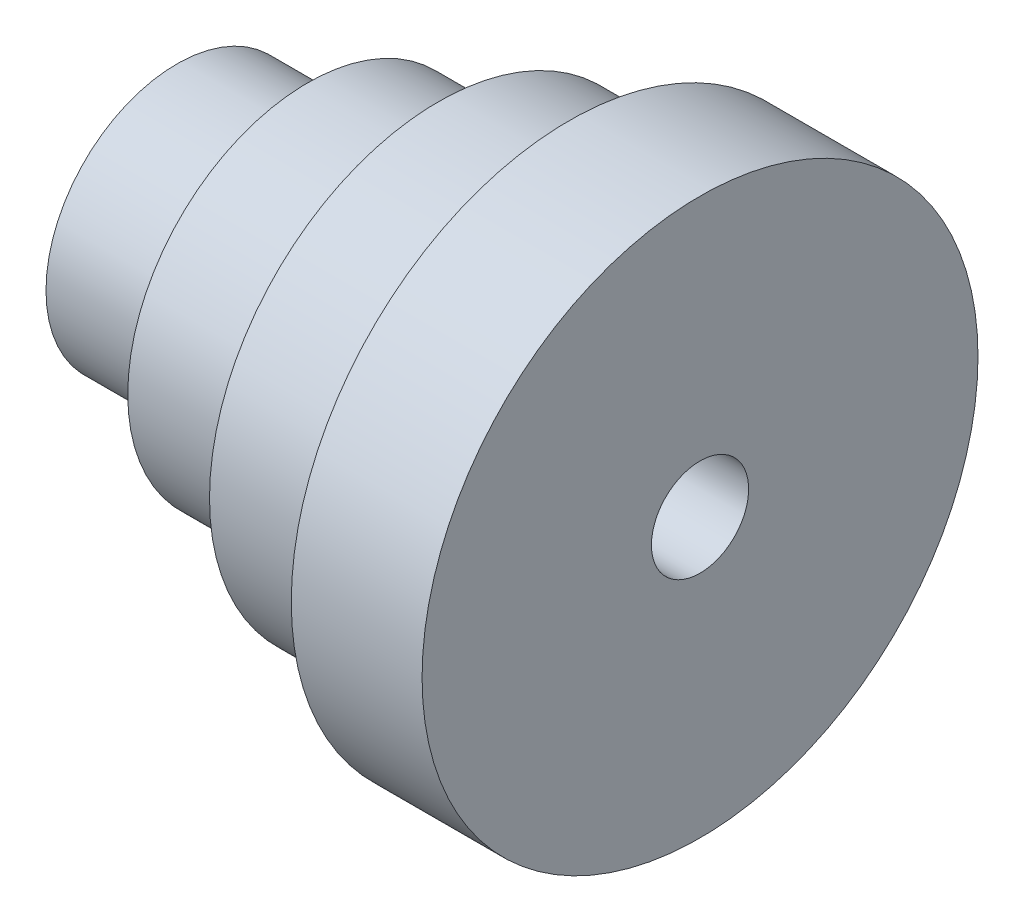
SolidWorks part; units mm, degrees
ref_plane "Front Plane" through (0, 0, 0) normal (0, 0, 1) x (1, 0, 0)
ref_plane "Top Plane" through (0, 0, 0) normal (0, 1, 0) x (1, 0, 0)
ref_plane "Right Plane" through (0, 0, 0) normal (1, 0, 0) x (0, 0, -1)
sketch "Sketch1" plane through (0, 0, 0) normal (0, 0, 1) x (1, 0, 0)
  line L0 (-176, 0) -> (149.7143, 0) construction
  line L1 (-176, 40) -> (-176, 22.8571)
  line L2 (-176, 40) -> (-136, 40)
  line L3 (-136, 40) -> (-136, 55)
  line L4 (-136, 55) -> (-96, 55)
  line L5 (-96, 55) -> (-96, 70)
  line L6 (-96, 70) -> (-56, 70)
  line L7 (-56, 70) -> (-56, 85)
  line L8 (-56, 85) -> (-16, 85)
  line L9 (-16, 85) -> (-16, 0)
  line L10 (-16, 77) -> (-48, 77)
  line L11 (-48, 77) -> (-48, 62)
  line L12 (-48, 62) -> (-88, 62)
  line L13 (-88, 62) -> (-88, 47)
  line L14 (-88, 47) -> (-128, 47)
  line L15 (-128, 47) -> (-128, 37.1429)
  line L16 (-128, 37.1429) -> (-45.1429, 37.1429)
  line L17 (-45.1429, 37.1429) -> (-45.1429, 22.8571)
  line L18 (-45.1429, 22.8571) -> (-176, 22.8571)
  line L19 (-176, 14.8677) -> (-16, 14.8677)
  line L20 (-45.1429, 22.8571) -> (-16, 22.8571)
  line L21 (-176, 14.8677) -> (-176, 0)
  line L22 (-176, 22.8571) -> (-176, 14.8677)
  point P23 (-76, 70)
  dimension "D1" = 40
  dimension "D2" = 40
  dimension "D3" = 40
  dimension "D4" = 40
  dimension "D5" = 8
  dimension "D6" = 8
  dimension "D7" = 8
  dimension "D8" = 8
  dimension "D9" = 8
  dimension "D10" = 8
  dimension "D12" = 40
  dimension "D13" = 55
  dimension "D14" = 70
  dimension "D15" = 85
revolve "Revolve2" add sketch "Sketch1" angle 360 about L0
sketch "Sketch2" plane through (-176, 0, 0) normal (-1, 0, 0) x (0, 0, 1)
  line L1 (-3, -9.8677) -> (3, -9.8677)
  line L2 (-3, -9.8677) -> (-3, -19.8677)
  line L3 (-3, -19.8677) -> (3, -19.8677)
  line L4 (3, -9.8677) -> (3, -19.8677)
  line L5 (-3, -9.8677) -> (3, -19.8677) construction
  line L6 (-3, -19.8677) -> (3, -9.8677) construction
  circle A0 centre (0, 0) radius 14.8677 construction
  point P0 (0, -14.8677)
  dimension "D1" = 5
  dimension "D2" = 6
extrude "Cut-Extrude3" cut sketch "Sketch2" against normal blind 100
